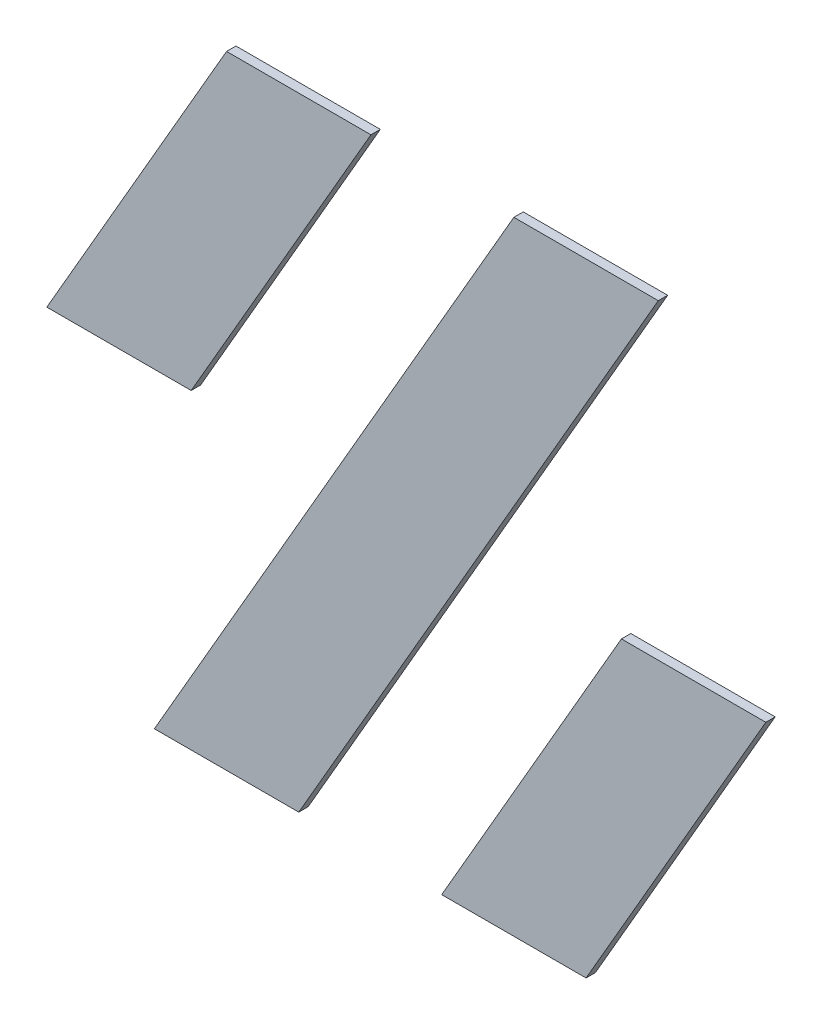
SolidWorks part; units mm, degrees
ref_plane "Piano frontale" through (0, 0, 0) normal (0, 0, 1) x (1, 0, 0)
ref_plane "Piano superiore" through (0, 0, 0) normal (0, 1, 0) x (1, 0, 0)
ref_plane "Piano destro" through (0, 0, 0) normal (1, 0, 0) x (0, 0, -1)
sketch "Schizzo1" plane through (0, 0, 0) normal (0, 0, 1) x (1, 0, 0)
  line L0 (-1.1312, 9.9593) -> (-6.8812, 0)
  line L1 (11.5, 0) -> (5.75, 9.9593) construction
  line L2 (5.75, 9.9593) -> (-5.75, 9.9593) construction
  line L3 (-5.75, 9.9593) -> (-11.5, 0)
  line L4 (-11.5, 0) -> (-5.75, -9.9593) construction
  line L5 (-5.75, -9.9593) -> (5.75, -9.9593) construction
  line L6 (5.75, -9.9593) -> (11.5, 0)
  line L7 (-6.8812, 0) -> (-11.5, 0)
  line L8 (11.5, 0) -> (6.8812, 0)
  line L9 (6.8812, 0) -> (1.1312, -9.9593)
  line L10 (3.4414, 9.9593) -> (8.0602, 9.9593)
  line L11 (8.0602, 9.9593) -> (-3.4398, -9.9593)
  line L12 (-3.4398, -9.9593) -> (-8.0586, -9.9593)
  line L13 (-8.0586, -9.9593) -> (3.4414, 9.9593)
  line L14 (-5.75, 9.9593) -> (-1.1312, 9.9593)
  line L15 (1.1312, -9.9593) -> (5.75, -9.9593)
  circle A0 centre (0, 0) radius 9.9593 construction
  dimension "D1" = 23
  dimension "D2" = 4
  dimension "D3" = 4
  dimension "D4" = 4
  dimension "D5" = 3.96
extrude "Estrusione-Estrusione1" add sketch "Schizzo1" against normal blind 0.3
